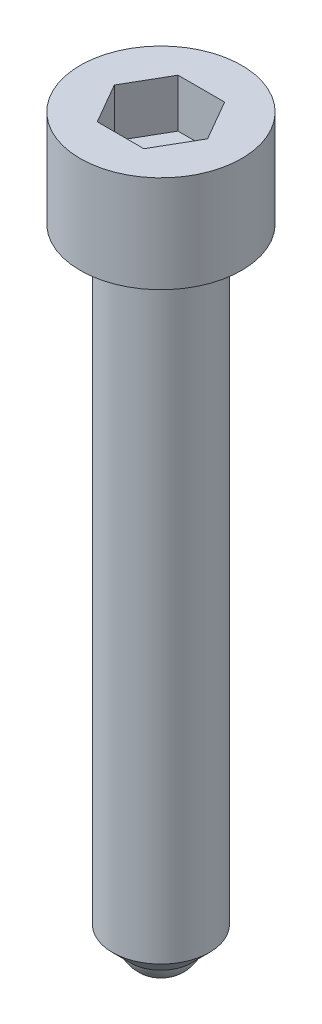
SolidWorks part; units mm, degrees
material "AISI 304"
ref_plane "Front Plane" through (0, 0, 0) normal (0, 0, 1) x (1, 0, 0)
ref_plane "Top Plane" through (0, 0, 0) normal (0, 1, 0) x (1, 0, 0)
ref_plane "Right Plane" through (0, 0, 0) normal (1, 0, 0) x (0, 0, -1)
sketch "Sketch1" plane through (0, 0, 0) normal (0, 0, 1) x (1, 0, 0)
  line L0 (0, 61.6916) -> (0, -59.3578) construction
  line L1 (0, -40) -> (3, -40) construction
  line L2 (3, -37.5735) -> (3, 0)
  line L3 (3, 0) -> (5, 0)
  line L4 (5, 0) -> (5, 6)
  line L5 (5, 6) -> (0, 6)
  line L6 (0, 6) -> (0, -40)
  line L7 (1.8735, -38.7) -> (3, -37.5735)
  arc A0 (0, -40) -> (1.8735, -38.7) centre (0, -38) ccw
  dimension "D6" = 2
  dimension "D1" = 40
  dimension "D2" = 10
  dimension "D3" = 6
  dimension "D4" = 6
  dimension "D5" = 45
  dimension "D7" = 1.3
revolve "Revolve1" add sketch "Sketch1" angle 360 about L0
sketch "Sketch2" plane through (0, 6, 0) normal (0, 1, 0) x (-1, 0, 0)
  line L1 (-1.4434, -2.5) -> (1.4434, -2.5)
  line L2 (1.4434, -2.5) -> (2.8868, 0)
  line L3 (2.8868, 0) -> (1.4434, 2.5)
  line L4 (1.4434, 2.5) -> (-1.4434, 2.5)
  line L5 (-1.4434, 2.5) -> (-2.8868, 0)
  line L6 (-2.8868, 0) -> (-1.4434, -2.5)
  circle A0 centre (0, 0) radius 2.5 construction
  dimension "D1" = 5
extrude "Cut-Extrude1" cut sketch "Sketch2" against normal blind 3
